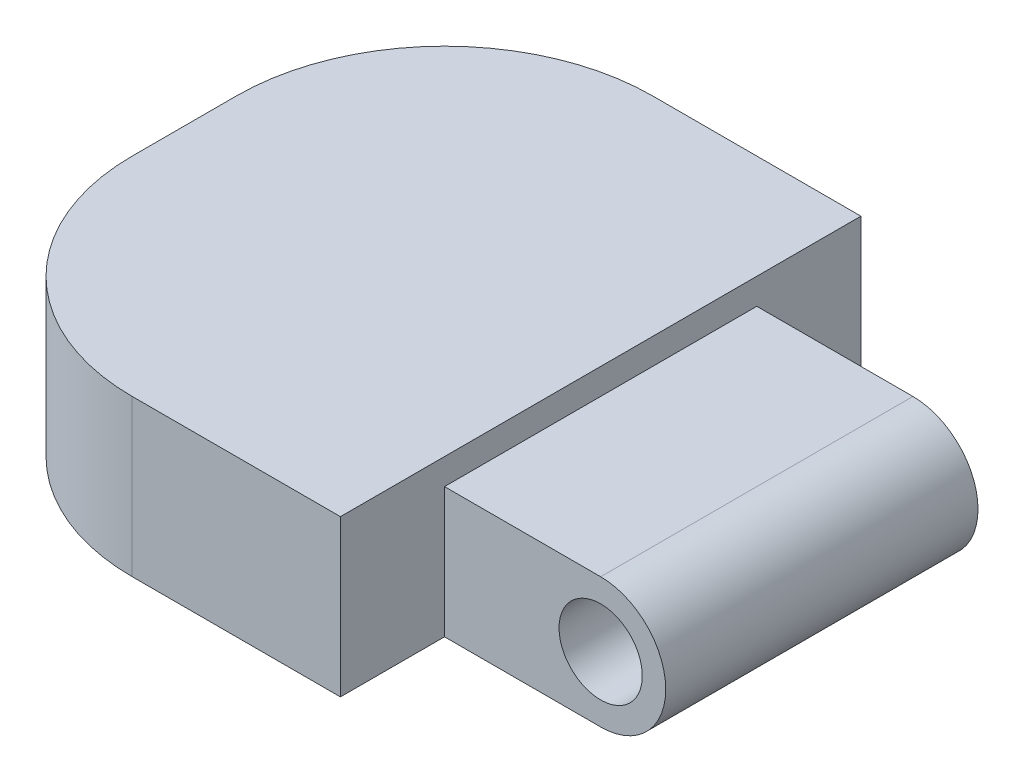
SolidWorks part; units mm, degrees
material "Plain Carbon Steel"
ref_plane "Front Plane" through (0, 0, 0) normal (0, 0, 1) x (1, 0, 0)
ref_plane "Top Plane" through (0, 0, 0) normal (0, 1, 0) x (1, 0, 0)
ref_plane "Right Plane" through (0, 0, 0) normal (1, 0, 0) x (0, 0, -1)
sketch "Sketch1" plane through (0, 0, 0) normal (0, 1, 0) x (1, 0, 0)
  line L1 (50.8, 63.5) -> (0, 63.5)
  line L2 (50.8, 63.5) -> (50.8, -63.5)
  line L3 (50.8, -63.5) -> (0, -63.5)
  line L4 (-50.8, 12.7) -> (-50.8, -12.7)
  line L5 (50.8, 63.5) -> (-50.8, -63.5) construction
  line L6 (50.8, -63.5) -> (-50.8, 63.5) construction
  arc A0 (0, -63.5) -> (-50.8, -12.7) centre (0, -12.7) cw
  arc A1 (0, 63.5) -> (-50.8, 12.7) centre (0, 12.7) ccw
  point P0 (0, 0)
  dimension "D3" = 50.8
  dimension "D1" = 101.6
  dimension "D2" = 127
extrude "Boss-Extrude1" add sketch "Sketch1" along normal blind 38.1
sketch "Sketch2" plane through (0, 0, 0) normal (0, 0, 1) x (1, 0, 0)
  line L0 (50.8, 31.75) -> (88.9, 31.75)
  line L1 (50.8, 38.1) -> (50.8, 0) construction
  line L2 (50.8, 31.75) -> (50.8, 0)
  line L3 (50.8, 0) -> (88.9, 0)
  line L4 (0, 0) -> (50.8, 0) construction
  arc A0 (88.9, 31.75) -> (88.9, 0) centre (88.9, 15.875) cw
  dimension "D1" = 6.35
  dimension "D2" = 38.1
extrude "Boss-Extrude2" add sketch "Sketch2" along normal blind 38.1 and the other way blind 38.1
sketch "Sketch3" plane through (0, 0, -38.1) normal (0, 0, -1) x (-1, 0, 0)
  circle A0 centre (-88.9, 15.875) radius 10.16
  dimension "D1" = 20.32
extrude "Cut-Extrude1" cut sketch "Sketch3" against normal through all
